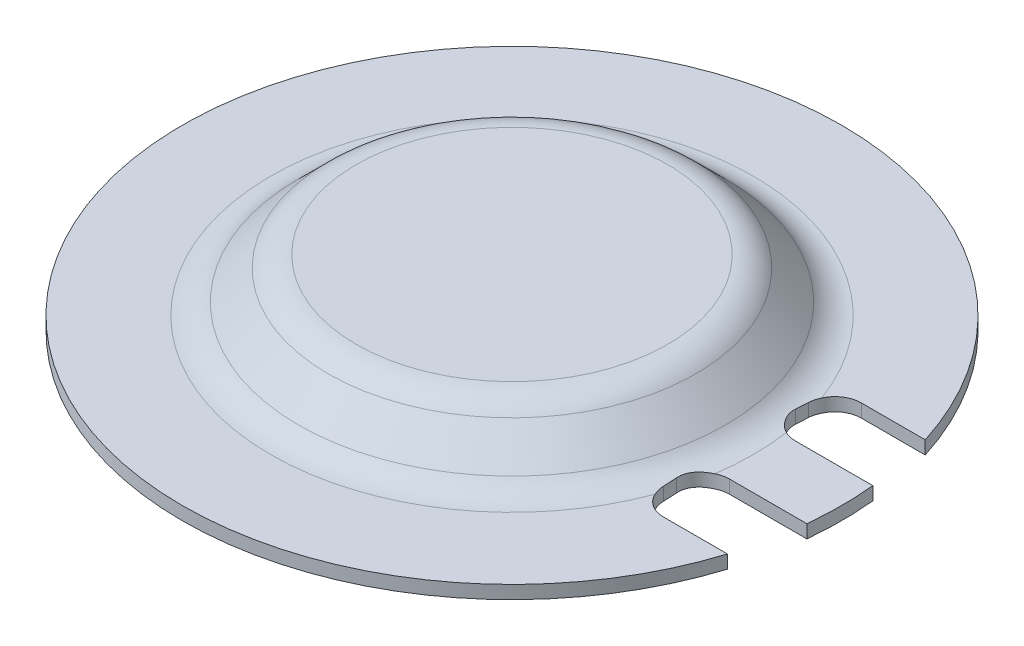
SolidWorks part; units mm, degrees
ref_plane "Front Plane" through (0, 0, 0) normal (0, 0, 1) x (1, 0, 0)
ref_plane "Top Plane" through (0, 0, 0) normal (0, 1, 0) x (1, 0, 0)
ref_plane "Right Plane" through (0, 0, 0) normal (1, 0, 0) x (0, 0, -1)
sketch "Sketch1" plane through (0, 0, 0) normal (0, 0, 1) x (1, 0, 0)
  line L0 (2.159, 17.2698) -> (2.159, 17.1428) construction
  line L1 (2.413, 18.7938) -> (3.0288, 18.7938) construction
  line L2 (2.413, 16.8888) -> (3.0288, 16.8888) construction
  line L3 (2.159, 18.5398) -> (2.159, 18.4128) construction
  line L4 (2.413, 17.5238) -> (3.1591, 17.5238) construction
  line L5 (2.413, 18.1588) -> (3.1591, 18.1588) construction
  line L6 (-0.2, 17.8413) -> (0.2, 17.8413) construction
  line L7 (0, 17.6412) -> (0, 18.0413) construction
  line L8 (1.4325, 7.8463) -> (-0.0679, 7.8463)
  line L9 (2.2562, 7.2113) -> (3.1069, 7.2113)
  line L10 (-0.0679, 7.8463) -> (-0.0679, 7.732)
  line L12 (3.1069, 7.3383) -> (2.2562, 7.3383)
  line L13 (3.1069, 7.3383) -> (3.1069, 7.2113)
  line L15 (1.9868, 7.4498) -> (1.7019, 7.7347)
  line L16 (1.4325, 7.732) -> (-0.0679, 7.732)
  line L17 (1.9059, 7.369) -> (1.6211, 7.6538)
  line L19 (-0.0679, 7.8463) -> (-0.0679, 6.4919) construction
  arc A0 (3.0288, 18.7938) -> (3.0288, 16.8888) centre (0, 17.8413) ccw construction
  arc A1 (3.1591, 17.5238) -> (3.1591, 18.1588) centre (0, 17.8413) ccw construction
  circle A2 centre (0.0002, 17.8413) radius 1.9123 construction
  arc A3 (2.413, 18.7938) -> (2.159, 18.5398) centre (2.413, 18.5398) ccw construction
  arc A4 (2.159, 18.4128) -> (2.413, 18.1588) centre (2.413, 18.4128) ccw construction
  arc A5 (2.413, 17.5238) -> (2.159, 17.2698) centre (2.413, 17.2698) ccw construction
  arc A6 (2.159, 17.1428) -> (2.413, 16.8888) centre (2.413, 17.1428) ccw construction
  arc A7 (1.7019, 7.7347) -> (1.4325, 7.8463) centre (1.4325, 7.4653) ccw
  arc A8 (1.9868, 7.4498) -> (2.2562, 7.3383) centre (2.2562, 7.7193) ccw
  arc A11 (1.6211, 7.6538) -> (1.4325, 7.732) centre (1.4325, 7.4653) ccw
  arc A12 (1.9059, 7.369) -> (2.2562, 7.2113) centre (2.2742, 7.719) ccw
revolve "Revolve2" add sketch "Sketch1" angle 360 about L19
sketch "Sketch2" plane through (0, 7.2113, 0) normal (0, -1, 0) x (1, 0, 0)
  line L0 (2.0909, -0.5715) -> (2.0909, -0.6985)
  line L1 (2.3449, 0.9525) -> (3.6345, 0.9525)
  line L2 (2.3449, -0.9525) -> (3.6345, -0.9525)
  line L3 (2.0909, 0.6985) -> (2.0909, 0.5715)
  line L4 (2.3449, -0.3175) -> (3.6345, -0.3175)
  line L5 (2.3449, 0.3175) -> (3.6345, 0.3175)
  line L6 (-0.2682, 0) -> (0.1319, 0) construction
  line L7 (-0.0681, -0.2) -> (-0.0681, 0.2) construction
  line L8 (3.6345, 0.9525) -> (3.6345, 0.3175)
  line L9 (3.6345, -0.3175) -> (3.6345, -0.9525)
  arc A1 (3.0909, -0.3175) -> (3.0909, 0.3175) centre (-0.0681, 0) ccw construction
  circle A2 centre (-0.0679, 0) radius 1.9123 construction
  arc A3 (2.3449, 0.9525) -> (2.0909, 0.6985) centre (2.3449, 0.6985) ccw
  arc A4 (2.0909, 0.5715) -> (2.3449, 0.3175) centre (2.3449, 0.5715) ccw
  arc A5 (2.3449, -0.3175) -> (2.0909, -0.5715) centre (2.3449, -0.5715) ccw
  arc A6 (2.0909, -0.6985) -> (2.3449, -0.9525) centre (2.3449, -0.6985) ccw
extrude "Cut-Extrude1" cut sketch "Sketch2" against normal through all
